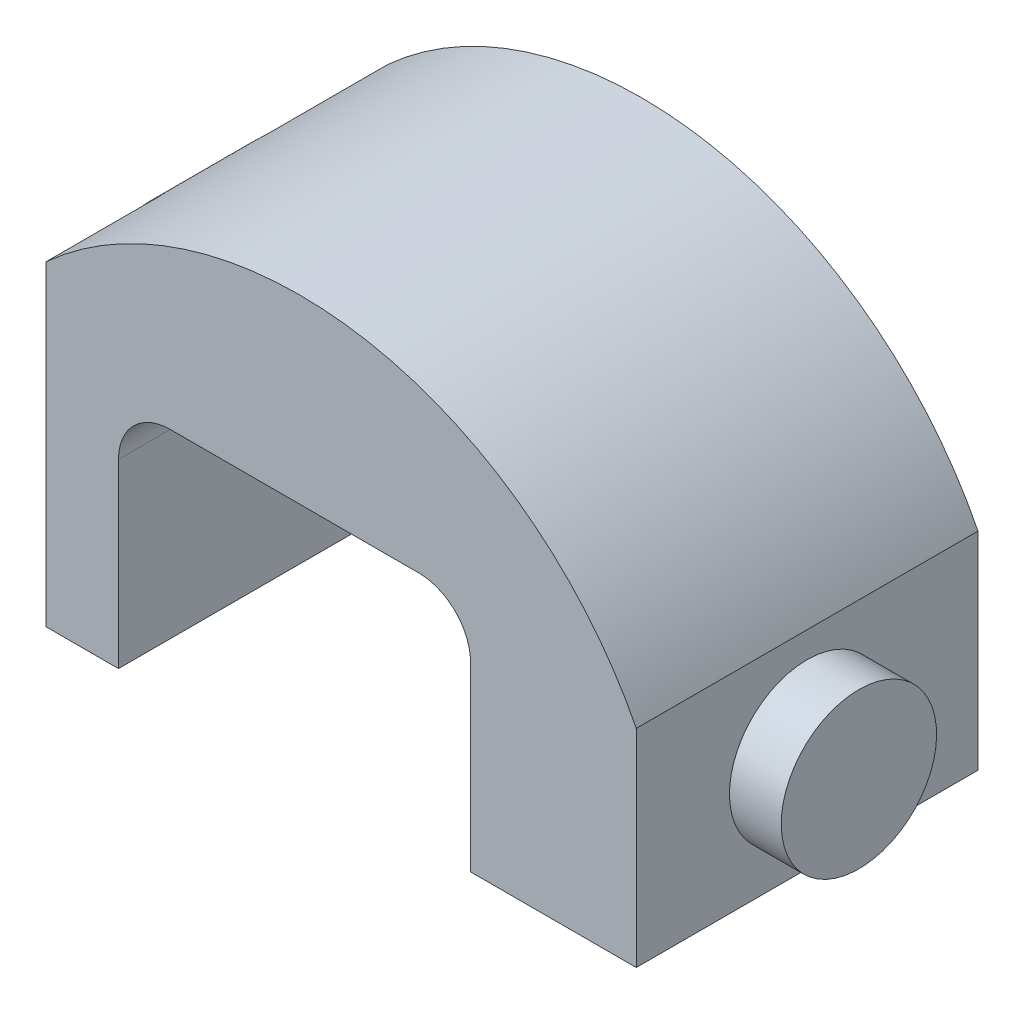
SolidWorks part; units mm, degrees
ref_plane "Front Plane" through (0, 0, 0) normal (0, 0, 1) x (1, 0, 0)
ref_plane "Top Plane" through (0, 0, 0) normal (0, 1, 0) x (1, 0, 0)
ref_plane "Right Plane" through (0, 0, 0) normal (1, 0, 0) x (0, 0, -1)
sketch "Sketch2" plane through (0, 0, 0) normal (0, 0, 1) x (1, 0, 0)
  line L1 (-65, 40) -> (65, 40)
  line L2 (-65, 40) -> (-65, -40)
  line L3 (-65, -40) -> (65, -40)
  line L4 (65, 40) -> (65, -40)
  line L5 (-65, 40) -> (65, -40) construction
  line L6 (-65, -40) -> (65, 40) construction
  arc A0 (-65, 0) -> (65, 0) centre (0, -32.8125) cw
  point P0 (0, 0)
  dimension "D1" = 130
  dimension "D2" = 80
extrude "Boss-Extrude1" add sketch "Sketch2" along normal blind 66 contours A0 L2 L3 L4
sketch "Sketch4" plane through (65, 0, 0) normal (1, 0, 0) x (0, 0, -1)
  line L0 (-66, 0) -> (0, 0) construction
  line L2 (0, 0) -> (0, -40) construction
  circle A0 centre (-33, -20) radius 15
  dimension "D1" = 30
  dimension "D2" = 20
  dimension "D3" = 33
extrude "Boss-Extrude2" add sketch "Sketch4" along normal blind 10
sketch "Sketch3" plane through (0, 0, 66) normal (0, 0, 1) x (1, 0, 0)
  line L0 (-65, -40) -> (65, -40) construction
  line L1 (-25, 5) -> (23, 5)
  line L2 (-35, -5) -> (-35, -40)
  line L3 (-35, -40) -> (33, -40)
  line L4 (33, -5) -> (33, -40)
  line L5 (-65, 0) -> (-65, -40) construction
  line L6 (65, 0) -> (65, -40) construction
  arc A1 (23, 5) -> (33, -5) centre (23, -5) cw
  arc A2 (-35, -5) -> (-25, 5) centre (-25, -5) cw
  point P12 (33, 5)
  dimension "D2" = 32
  dimension "D4" = 10
  dimension "D1" = 30
  dimension "D3" = 45
extrude "Cut-Extrude2" cut sketch "Sketch3" against normal through all
sketch "Sketch5" plane through (0, -40, 0) normal (0, -1, 0) x (1, 0, 0)
  line L9 (-65, 66) -> (-49, 66)
  line L10 (-65, 66) -> (-65, 43)
  line L11 (-65, 43) -> (-49, 43)
  line L12 (-49, 66) -> (-49, 43)
  line L13 (-65, 0) -> (-49, 0)
  line L14 (-65, 0) -> (-65, 23)
  line L15 (-65, 23) -> (-49, 23)
  line L16 (-49, 0) -> (-49, 23)
  dimension "D1" = 16
  dimension "D2" = 16
  dimension "D3" = 23
  dimension "D4" = 23
extrude "Cut-Extrude3" cut sketch "Sketch5" against normal through all
sketch "Sketch6" plane through (0, -40, 0) normal (0, -1, 0) x (1, 0, 0)
  line L0 (-65, 43) -> (-65, 23) construction
  line L1 (-53.5, 38) -> (-43.5, 38)
  line L2 (-53.5, 38) -> (-53.5, 28)
  line L3 (-53.5, 28) -> (-43.5, 28)
  line L4 (-43.5, 38) -> (-43.5, 28)
  line L5 (-65, 43) -> (-49, 43) construction
  dimension "D1" = 10
  dimension "D2" = 10
  dimension "D3" = 11.5
  dimension "D4" = 5
extrude "Boss-Extrude3" add sketch "Sketch6" along normal blind 5
sketch "Sketch7" plane through (0, -40, 0) normal (0, -1, 0) x (1, 0, 0)
  line L0 (65, 66) -> (65, 0) construction
  line L1 (35.5, 19.9) -> (47.5, 19.9)
  line L2 (35.5, 19.9) -> (35.5, 7.9)
  line L3 (35.5, 7.9) -> (47.5, 7.9)
  line L4 (47.5, 19.9) -> (47.5, 7.9)
  line L5 (33, 0) -> (65, 0) construction
  line L7 (47.5, 19.9) -> (47.5, 46.1) construction
  line L9 (47.5, 46.1) -> (35.5, 46.1)
  line L10 (47.5, 46.1) -> (47.5, 58.1)
  line L11 (47.5, 58.1) -> (35.5, 58.1)
  line L12 (35.5, 46.1) -> (35.5, 58.1)
  dimension "D1" = 17.5
  dimension "D2" = 7.9
  dimension "D3" = 12
  dimension "D4" = 26.2
  dimension "D5" = 12
extrude "Boss-Extrude4" add sketch "Sketch7" along normal blind 5
